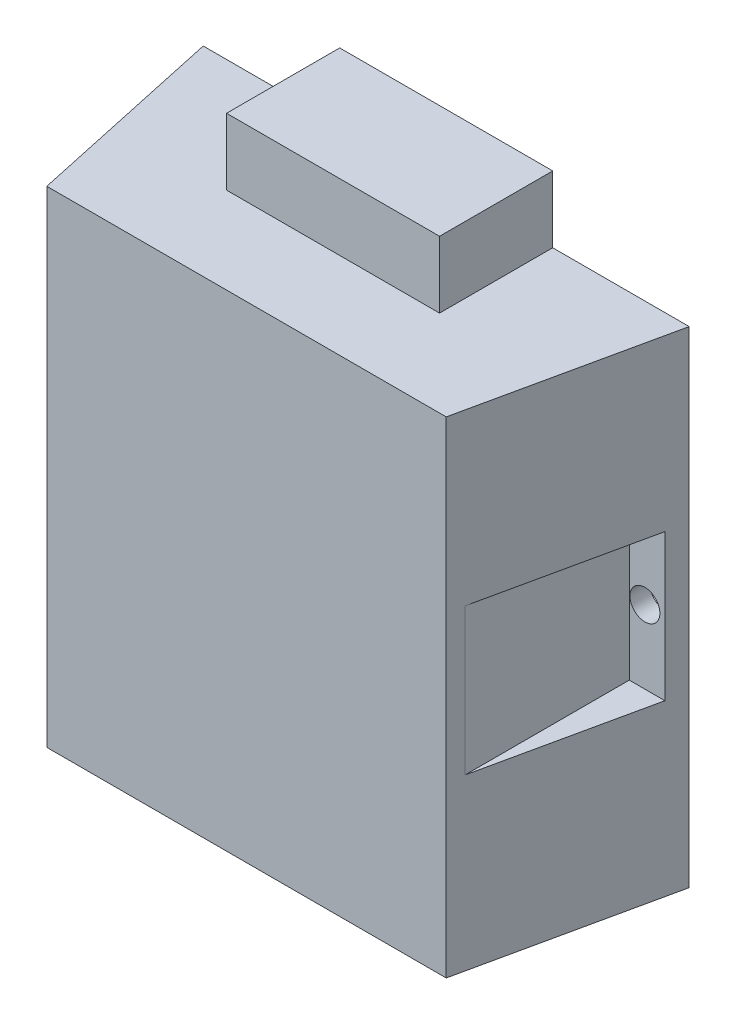
SolidWorks part; units mm, degrees
ref_plane "前视基准面" through (0, 0, 0) normal (0, 0, 1) x (1, 0, 0)
ref_plane "上视基准面" through (0, 0, 0) normal (0, 1, 0) x (1, 0, 0)
ref_plane "右视基准面" through (0, 0, 0) normal (1, 0, 0) x (0, 0, -1)
sketch "草图1" plane through (0, 0, 0) normal (0, 1, 0) x (1, 0, 0)
  line L0 (0, 0) -> (0, 57.8226) construction
  line L1 (-36.5, 30) -> (36.5, 30)
  line L2 (36.5, 30) -> (30, 0)
  line L3 (30, 0) -> (-30, 0)
  line L4 (-30, 0) -> (-36.5, 30)
  point P8 (0, 0)
  point P10 (0, 30)
  dimension "D1" = 30
  dimension "D2" = 60
  dimension "D3" = 73
extrude "凸台-拉伸1" add sketch "草图1" along normal blind 73
sketch "草图2" plane through (0, 73, 0) normal (0, 1, 0) x (1, 0, 0)
  line L0 (36.5, 30) -> (-36.5, 30) construction
  line L1 (-16, 13) -> (16, 13)
  line L2 (-16, 13) -> (-16, 30)
  line L3 (-16, 30) -> (16, 30)
  line L4 (16, 13) -> (16, 30)
  line L5 (-16, 13) -> (16, 30) construction
  line L6 (-16, 30) -> (16, 13) construction
  line L7 (-30, 0) -> (30, 0) construction
  point P0 (0, 21.5)
  point P10 (0, 30)
  point P11 (0, 0)
  dimension "D1" = 17
  dimension "D2" = 32
extrude "凸台-拉伸2" add sketch "草图2" along normal blind 10
ref_plane "基准面1" through (0, 0, -27) normal (0, 0, -1) x (-1, 0, 0)
sketch "草图3" plane through (0, 0, -27) normal (0, 0, -1) x (-1, 0, 0)
  line L0 (-36.5, 73) -> (-36.5, 0) construction
  line L1 (-36.5, 47.5) -> (-36.5, 25.5)
  line L2 (-36.5, 47.5) -> (-30.5, 47.5)
  line L3 (-30.5, 47.5) -> (-30.5, 25.5)
  line L4 (-30.5, 25.5) -> (-36.5, 25.5)
  line L5 (0, 12.6098) -> (0, 68.9217) construction
  line L6 (36.5, 47.5) -> (36.5, 25.5)
  line L7 (36.5, 47.5) -> (30.5, 47.5)
  line L8 (30.5, 25.5) -> (36.5, 25.5)
  line L9 (30.5, 47.5) -> (30.5, 25.5)
  point P4 (-36.5, 36.5)
  point P7 (-30.5, 36.5)
  point P13 (-36.5, 36.5)
  dimension "D1" = 22
  dimension "D2" = 6
extrude "切除-拉伸1" cut sketch "草图3" against normal through all
sketch "草图4" plane through (0, 0, -27) normal (0, 0, 1) x (1, 0, 0)
  line L0 (-35.85, 25.5) -> (-35.85, 47.5) construction
  line L1 (35.85, 25.5) -> (35.85, 47.5) construction
  circle A0 centre (32.85, 36.5) radius 2.25
  circle A1 centre (-32.85, 36.5) radius 2.25
  point P10 (-35.85, 36.5)
  dimension "D2" = 4.5
  dimension "D3" = 3
  dimension "D1" = 3
extrude "切除-拉伸2" cut sketch "草图4" against normal blind 10
